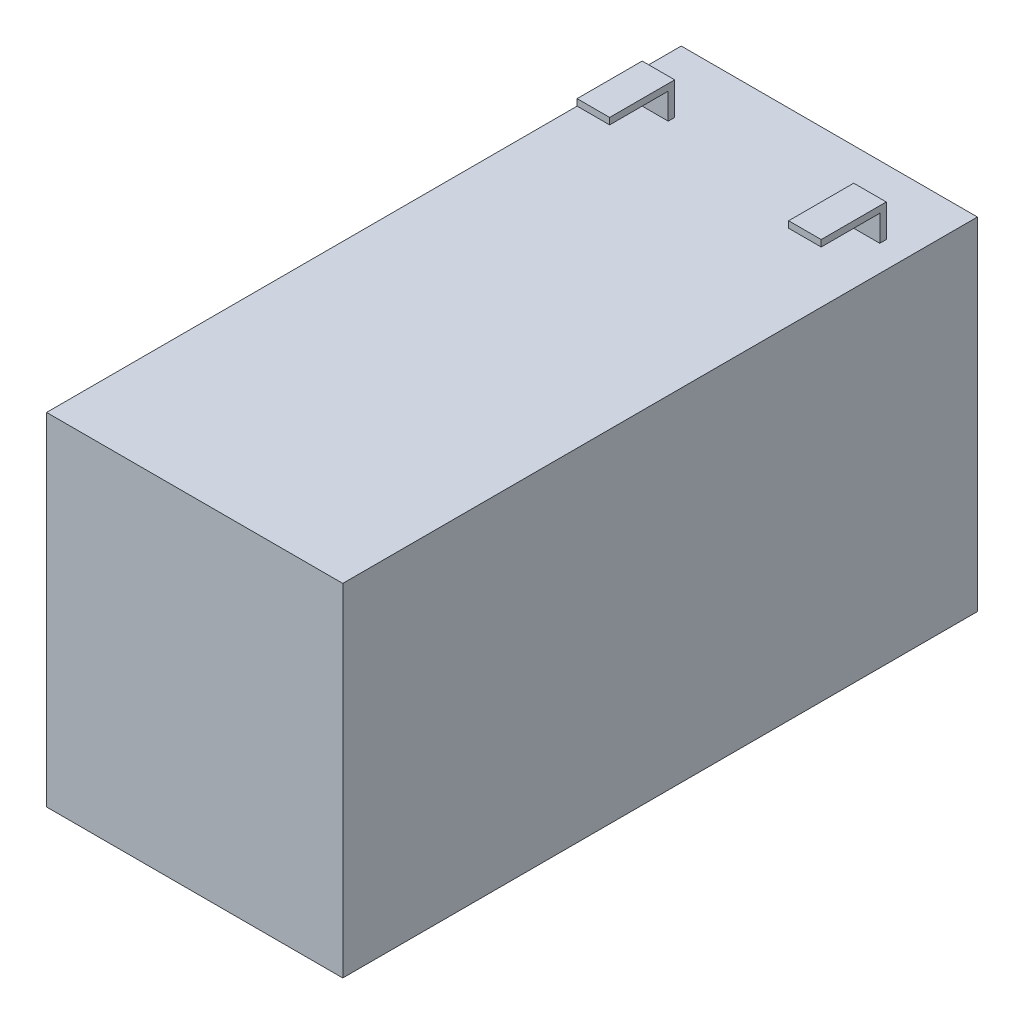
SolidWorks part; units mm, degrees
ref_plane "前视基准面" through (0, 0, 0) normal (0, 0, 1) x (1, 0, 0)
ref_plane "上视基准面" through (0, 0, 0) normal (0, 1, 0) x (1, 0, 0)
ref_plane "右视基准面" through (0, 0, 0) normal (1, 0, 0) x (0, 0, -1)
sketch "草图1" plane through (0, 0, 0) normal (0, 1, 0) x (1, 0, 0)
  line L0 (0, -83.4464) -> (0, 93.8761) construction
  line L1 (-22.75, -48.75) -> (22.75, -48.75)
  line L2 (-22.75, -48.75) -> (-22.75, 48.75)
  line L3 (-22.75, 48.75) -> (22.75, 48.75)
  line L4 (22.75, -48.75) -> (22.75, 48.75)
  line L5 (-72.4379, 0) -> (62.9653, 0) construction
  dimension "D1" = 97.5
  dimension "D2" = 45.5
extrude "拉伸1" add sketch "草图1" along normal blind 52.5
sketch "草图3" plane through (0, 52.5, 0) normal (0, 1, 0) x (-1, 0, 0)
  line L0 (-22.75, -48.75) -> (22.75, -48.75) construction
  line L1 (18.75, -38.75) -> (13.75, -38.75)
  line L2 (18.75, -38.75) -> (18.75, -37.75)
  line L3 (18.75, -37.75) -> (13.75, -37.75)
  line L4 (13.75, -38.75) -> (13.75, -37.75)
  line L5 (22.75, -48.75) -> (22.75, 48.75) construction
  dimension "D1" = 10
  dimension "D2" = 4
  dimension "D3" = 5
  dimension "D4" = 1
ref_plane "基准面1" through (-18.75, 0, 0) normal (-1, 0, 0) x (0, 0, 1)
sketch "草图4" plane through (-18.75, 0, 0) normal (-1, 0, 0) x (0, 0, 1)
  line L0 (-38.75, 52.5) -> (-38.75, 57.5)
  line L1 (-38.75, 57.5) -> (-28.75, 57.5)
  dimension "D1" = 10
  dimension "D2" = 5
sweep "扫描1" add profiles "草图3" path "草图4"
ref_plane "基准面2" through (0, 0, 0) normal (-1, 0, 0) x (0, 0, 1)
mirror "镜向2" about plane through (0, 0, 0) normal (-1, 0, 0) of "扫描1"
